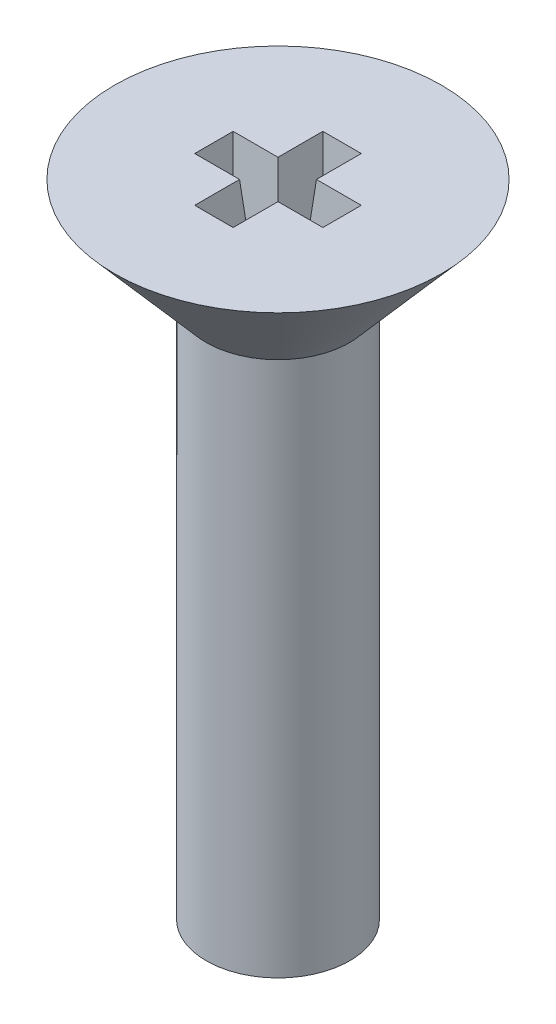
SolidWorks part; units mm, degrees
ref_plane "Front Plane" through (0, 0, 0) normal (0, 0, 1) x (1, 0, 0)
ref_plane "Top Plane" through (0, 0, 0) normal (0, 1, 0) x (1, 0, 0)
ref_plane "Right Plane" through (0, 0, 0) normal (1, 0, 0) x (0, 0, -1)
sketch "Sketch1" plane through (0, 0, 0) normal (0, 0, 1) x (1, 0, 0)
  line L1 (1.4224, 0) -> (3.2385, 2.0892)
  line L5 (3.2385, 2.0892) -> (0, 2.0892)
  line L6 (0, 2.0892) -> (0, 0)
  line L7 (0, 0) -> (0, -10.6108)
  line L8 (0, -10.6108) -> (1.4224, -10.6108)
  line L9 (1.4224, -10.6108) -> (1.4224, 0)
  line L11 (1.4224, 0) -> (0, 0) construction
  dimension "D1" = 12.7
  dimension "D2" = 1.4224
  dimension "D3" = 41
  dimension "D4" = 3.2385
revolve "Revolve1" add sketch "Sketch1" angle 360 about L7
sketch "Sketch2" plane through (0, 2.0892, 0) normal (0, 1, 0) x (1, 0, 0)
  line L0 (-0.381, 1.27) -> (0.381, 1.27)
  line L1 (0.381, 1.27) -> (0.381, 0.381)
  line L2 (0.381, 0.381) -> (1.27, 0.381)
  line L3 (1.27, 0.381) -> (1.27, -0.381)
  line L4 (1.27, -0.381) -> (0.381, -0.381)
  line L5 (0.381, -0.381) -> (0.381, -1.27)
  line L6 (0.381, -1.27) -> (-0.381, -1.27)
  line L7 (-0.381, -1.27) -> (-0.381, -0.381)
  line L8 (-0.381, -0.381) -> (-1.27, -0.381)
  line L9 (-1.27, -0.381) -> (-1.27, 0.381)
  line L10 (-1.27, 0.381) -> (-0.381, 0.381)
  line L11 (-0.381, 0.381) -> (-0.381, 1.27)
  line L12 (0, 1.27) -> (0, 0) construction
  line L13 (0, 0) -> (0, -1.27) construction
  line L14 (-1.27, 0) -> (0, 0) construction
  line L15 (1.27, 0) -> (0, 0) construction
  dimension "D1" = 0.762
  dimension "D2" = 1.27
extrude "Cut-Extrude1" cut sketch "Sketch2" against normal blind 2.159 draft 5
